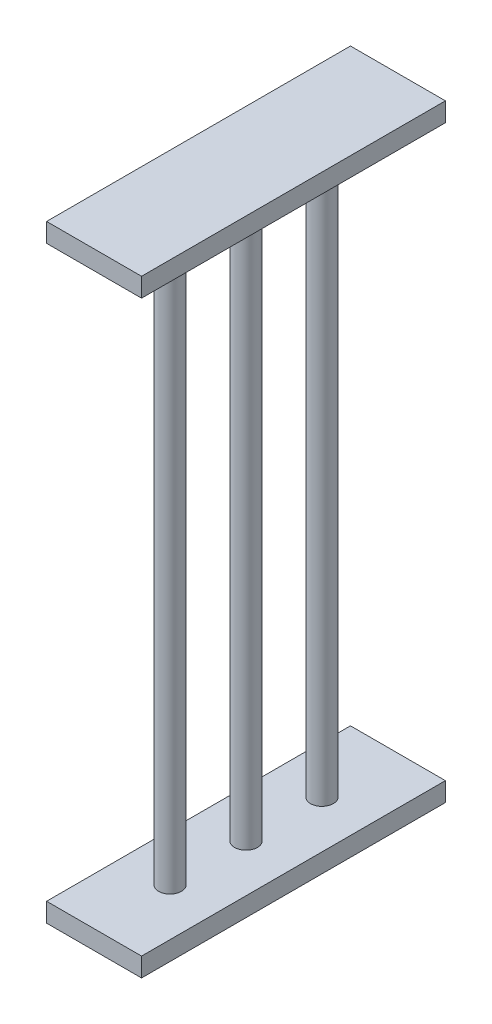
SolidWorks part; units mm, degrees
ref_plane "前视基准面" through (0, 0, 0) normal (0, 0, 1) x (1, 0, 0)
ref_plane "上视基准面" through (0, 0, 0) normal (0, 1, 0) x (1, 0, 0)
ref_plane "右视基准面" through (0, 0, 0) normal (1, 0, 0) x (0, 0, -1)
other "Configuration Table"
sketch "草图1" plane through (0, 0, 0) normal (0, 1, 0) x (1, 0, 0)
  line L1 (0, 0) -> (-50, 0)
  line L2 (0, 0) -> (0, 160)
  line L3 (0, 160) -> (-50, 160)
  line L4 (-50, 0) -> (-50, 160)
  dimension "D1" = 50
  dimension "D2" = 160
extrude "凸台-拉伸1" add sketch "草图1" along normal blind 10
sketch "草图2" plane through (0, 10, 0) normal (0, 1, 0) x (1, 0, 0)
  line L0 (-25, 160) -> (-25, -6.1632) construction
  line L1 (0, 160) -> (-50, 160) construction
  line L2 (-50, 0) -> (0, 0) construction
  circle A0 centre (-25, 120) radius 6
  circle A1 centre (-25, 80) radius 6
  circle A2 centre (-25, 40) radius 6
  dimension "D1" = 12
  dimension "D2" = 12
  dimension "D3" = 12
  dimension "D4" = 40
  dimension "D5" = 40
  dimension "D6" = 40
extrude "凸台-拉伸2" add sketch "草图2" along normal blind 300
sketch "草图3" plane through (0, 310, 0) normal (0, 1, 0) x (1, 0, 0)
  line L4 (0, 0) -> (0, 160)
  line L5 (0, 160) -> (-50, 160)
  line L6 (-50, 160) -> (-50, 0)
  line L7 (-50, 0) -> (0, 0)
  line L8 (0, 0) -> (0, 160)
  line L9 (0, 160) -> (-50, 160)
  line L10 (-50, 160) -> (-50, 0)
  line L11 (-50, 0) -> (0, 0)
  dimension "D1" = 0
extrude "凸台-拉伸3" add sketch "草图3" along normal blind 10
